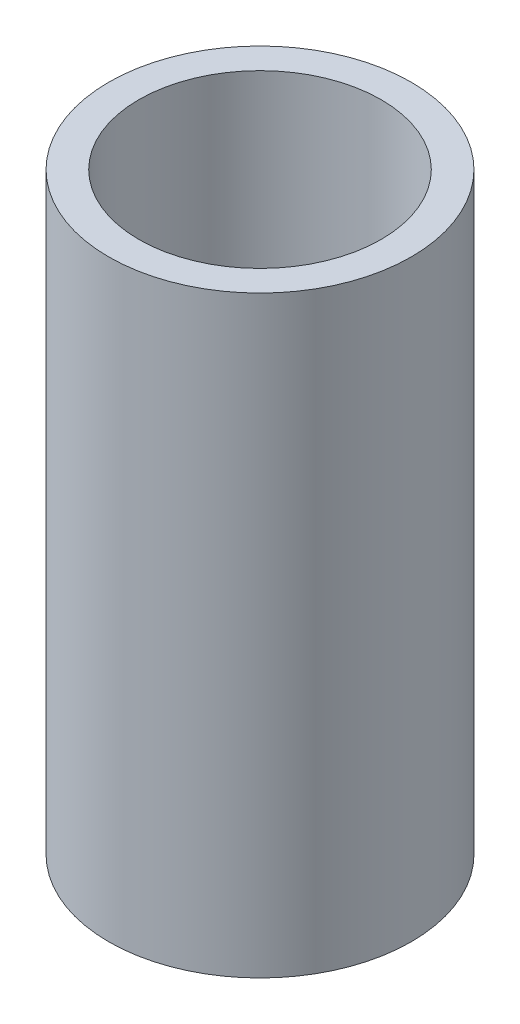
SolidWorks part; units mm, degrees
ref_plane "Front" through (0, 0, 0) normal (0, 0, 1) x (1, 0, 0)
ref_plane "Top" through (0, 0, 0) normal (0, 1, 0) x (1, 0, 0)
ref_plane "Right" through (0, 0, 0) normal (1, 0, 0) x (0, 0, -1)
sketch "Sketch1" plane through (0, 0, 0) normal (0, 1, 0) x (1, 0, 0)
  line L0 (0, 7.525) -> (0, 6.025) construction
  circle A0 centre (0, 0) radius 7.525
  circle A1 centre (0, 0) radius 6.025
  dimension "D1" = 12.05
  dimension "D2" = 1.5
extrude "Boss-Extrude1" add sketch "Sketch1" along normal blind 29.5
